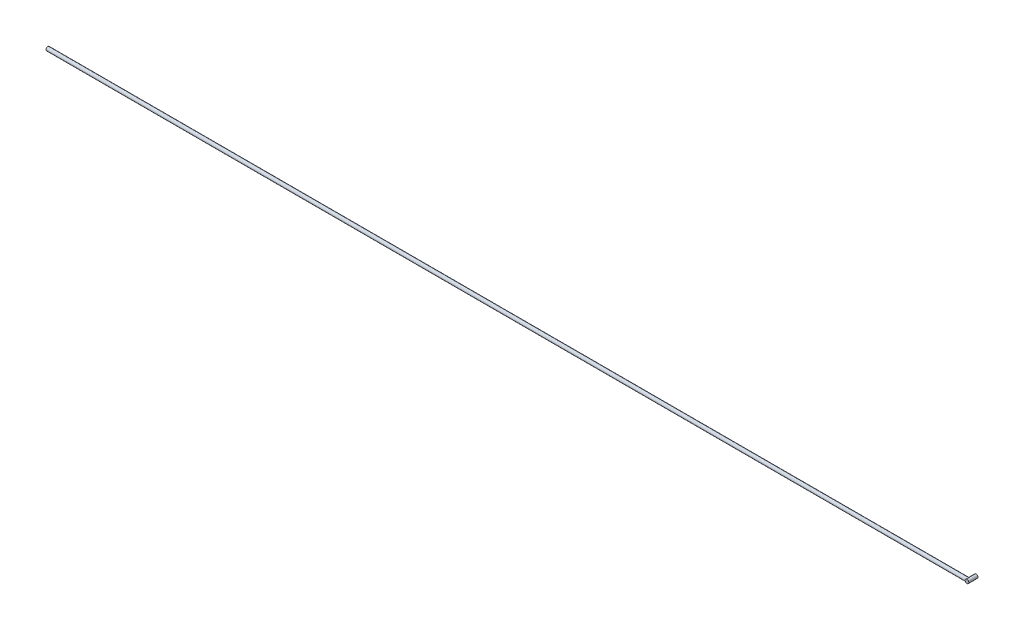
SolidWorks part; units mm, degrees
ref_plane "Plan de face" through (0, 0, 0) normal (0, 0, 1) x (1, 0, 0)
ref_plane "Plan de dessus" through (0, 0, 0) normal (0, 1, 0) x (1, 0, 0)
ref_plane "Plan de droite" through (0, 0, 0) normal (1, 0, 0) x (0, 0, -1)
sketch "Esquisse1" plane through (0, 0, 0) normal (0, 0, 1) x (1, 0, 0)
  line L0 (-250, 0) -> (250, 0)
  dimension "D1" = 500
sweep "Balayage1" add path "Esquisse1" circular profile diameter 2 parameters "D3"=2
sketch "Esquisse16" plane through (250, 0, 0) normal (1, 0, 0) x (0, 0, -1)
  line L0 (-1, 0) -> (4, 0)
  circle A1 centre (0, 0) radius 1 construction
  point P2 (0, 0)
  dimension "D1" = 5
sweep "Balayage2" add path "Esquisse16" circular profile diameter 2 parameters "D3"=2
